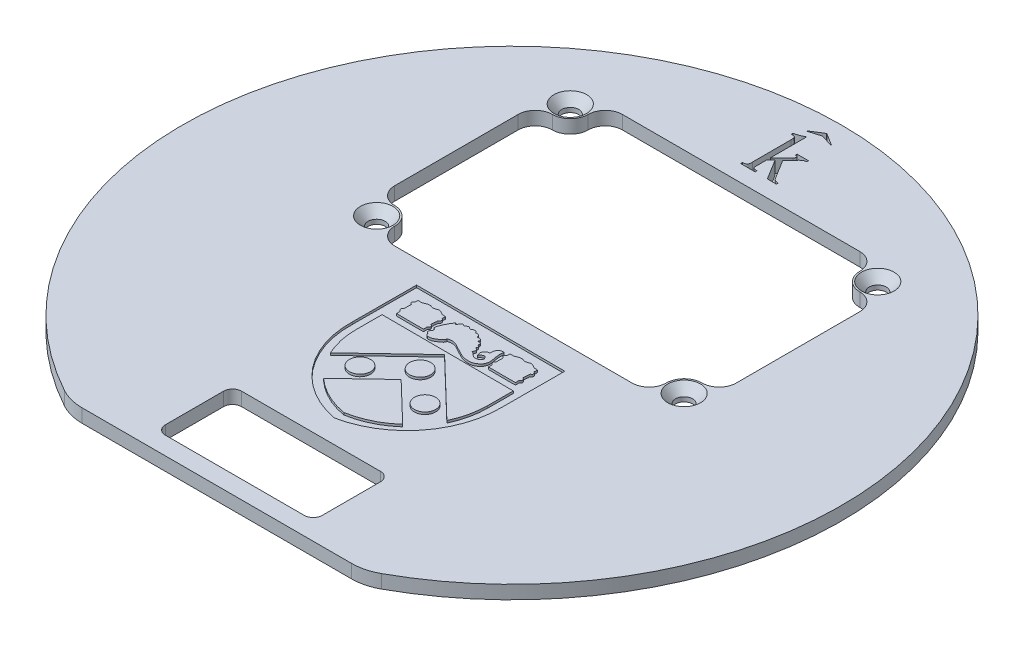
SolidWorks part; units mm, degrees
material "Acrylic (Medium-high impact)"
ref_plane "Front Plane" through (0, 0, 0) normal (0, 0, 1) x (1, 0, 0)
ref_plane "Top Plane" through (0, 0, 0) normal (0, 1, 0) x (1, 0, 0)
ref_plane "Right Plane" through (0, 0, 0) normal (1, 0, 0) x (0, 0, -1)
sketch "Sketch1" plane through (0, 0, 0) normal (0, 1, 0) x (1, 0, 0)
  line L0 (-30.03, -64.8129) -> (30.03, -64.8129) construction
  line L1 (0, -85) -> (0, 0) construction
  line L2 (0, -85) -> (32.4891, -64.8129) construction
  line L3 (-30.03, -65.8129) -> (30.03, -65.8129)
  arc A0 (34.8348, -63.5829) -> (-34.8348, -63.5829) centre (0, 0) ccw construction
  circle A1 centre (0, -85) radius 38.25 construction
  arc A2 (30.03, -64.8129) -> (34.8348, -63.5829) centre (30.03, -54.8129) ccw construction
  arc A3 (-30.03, -64.8129) -> (-34.8348, -63.5829) centre (-30.03, -54.8129) cw construction
  arc A4 (35.3153, -64.4599) -> (-35.3153, -64.4599) centre (0, 0) ccw
  arc A5 (-30.03, -65.8129) -> (-35.3153, -64.4599) centre (-30.03, -54.8129) cw
  arc A6 (30.03, -65.8129) -> (35.3153, -64.4599) centre (30.03, -54.8129) ccw
  dimension "D1" = 145
  dimension "D2" = 76.5
  dimension "D4" = 10
  dimension "D3" = 85
  dimension "D5" = 1
extrude "Boss-Extrude1" add sketch "Sketch1" along normal blind 3
sketch "Sketch2" plane through (0, 3, 0) normal (0, 1, 0) x (1, 0, 0)
  line L0 (-30.03, -65.8129) -> (30.03, -65.8129) construction
  line L1 (38.1, 0.3071) -> (-38.1, 0.3071) construction
  line L2 (38.1, 0.3071) -> (38.1, 51.1071) construction
  line L3 (38.1, 51.1071) -> (-38.1, 51.1071) construction
  line L4 (-38.1, 0.3071) -> (-38.1, 51.1071) construction
  line L5 (34.29, 4.1171) -> (-34.29, 4.1171) construction
  line L6 (-34.29, 4.1171) -> (-34.29, 47.2971) construction
  line L7 (34.29, 47.2971) -> (-34.29, 47.2971) construction
  line L8 (34.29, 4.1171) -> (34.29, 47.2971) construction
  line L9 (-38.1, 11.9271) -> (-38.1, 39.4871)
  line L10 (38.1, 11.9271) -> (38.1, 39.4871)
  line L11 (26.48, 51.1071) -> (-26.48, 51.1071)
  line L12 (-26.48, 0.3071) -> (26.48, 0.3071)
  line L14 (-15.5, -61.8129) -> (15.5, -61.8129)
  line L15 (-17.5, -59.8129) -> (-17.5, -46.8129)
  line L16 (-15.5, -44.8129) -> (15.5, -44.8129)
  line L17 (17.5, -59.8129) -> (17.5, -46.8129)
  circle A0 centre (34.29, 4.1171) radius 1.905
  circle A1 centre (-34.29, 4.1171) radius 1.905
  circle A2 centre (34.29, 47.2971) radius 1.905
  circle A3 centre (-34.29, 47.2971) radius 1.905
  arc A4 (30.29, 4.1171) -> (34.29, 8.1171) centre (34.29, 4.1171) cw
  arc A5 (34.29, 8.1171) -> (38.1, 11.9271) centre (34.29, 11.9271) ccw
  arc A6 (30.29, 4.1171) -> (26.48, 0.3071) centre (26.48, 4.1171) cw
  arc A7 (-38.1, 11.9271) -> (-34.29, 8.1171) centre (-34.29, 11.9271) ccw
  arc A8 (-34.29, 8.1171) -> (-30.29, 4.1171) centre (-34.29, 4.1171) cw
  arc A9 (-30.29, 4.1171) -> (-26.48, 0.3071) centre (-26.48, 4.1171) ccw
  arc A10 (-38.1, 39.4871) -> (-34.29, 43.2971) centre (-34.29, 39.4871) cw
  arc A11 (-34.29, 43.2971) -> (-30.29, 47.2971) centre (-34.29, 47.2971) ccw
  arc A12 (-30.29, 47.2971) -> (-26.48, 51.1071) centre (-26.48, 47.2971) cw
  arc A13 (38.1, 39.4871) -> (34.29, 43.2971) centre (34.29, 39.4871) ccw
  arc A14 (34.29, 43.2971) -> (30.29, 47.2971) centre (34.29, 47.2971) cw
  arc A15 (30.29, 47.2971) -> (26.48, 51.1071) centre (26.48, 47.2971) ccw
  arc A16 (15.5, -61.8129) -> (17.5, -59.8129) centre (15.5, -59.8129) ccw
  arc A17 (-15.5, -61.8129) -> (-17.5, -59.8129) centre (-15.5, -59.8129) cw
  arc A18 (-17.5, -46.8129) -> (-15.5, -44.8129) centre (-15.5, -46.8129) cw
  arc A19 (15.5, -44.8129) -> (17.5, -46.8129) centre (15.5, -46.8129) cw
  point P5 (0, 0.3071)
  point P8 (0, -65.8129)
  point P11 (0, 51.1071)
  point P46 (0, -61.8129)
  point P51 (17.5, -61.8129)
  point P56 (-17.5, -44.8129)
  point P59 (17.5, -44.8129)
  dimension "D5" = 3.81
  dimension "D6" = 4
  dimension "D10" = 2
  dimension "D1" = 66.12
  dimension "D2" = 76.2
  dimension "D3" = 50.8
  dimension "D7" = 17
  dimension "D8" = 35
  dimension "D9" = 4
  dimension "D4" = 3.81
extrude "Cut-Extrude1" cut sketch "Sketch2" against normal through all contours A2 | A1 | A0 | A14 A15 L11 A12 A11 A10 L9 A7 A8 A9 L12 A6 A4 A5 L10 A13 | L14 L17 L16 L15 | A3
sketch "Sketch3" plane through (0, 3, 0) normal (0, 1, 0) x (1, 0, 0)
  line L0 (0, 0.3071) -> (0, -4.8617) construction
  line L1 (-26.48, 0.3071) -> (26.48, 0.3071) construction
  line L2 (0, -39.644) -> (0, -44.8129) construction
  line L3 (-15.5, -44.8129) -> (15.5, -44.8129) construction
  line L4 (-31.076, 54.8036) -> (31.076, 54.8036) construction
  line L5 (26.48, 51.1071) -> (-26.48, 51.1071) construction
  line L6 (0, 54.8036) -> (0, 51.1071) construction
  line L7 (0, 51.1071) -> (0, 54.8036) construction
  line L8 (0, 54.8036) -> (0, 69.8036) construction
  line L9 (0, 69.8036) -> (0, 73.5) construction
  line L10 (-2.6931, 68.5353) -> (-0.0266, 70.2086)
  line L11 (0.0266, 70.2086) -> (2.6931, 68.5353)
  line L12 (2.6524, 68.445) -> (0, 69.2253)
  line L13 (0, 69.2253) -> (-2.6524, 68.445)
  line L14 (-3, 68.3428) -> (3, 68.3428) construction
  arc A0 (35.3153, -64.4599) -> (-35.3153, -64.4599) centre (0, 0) ccw construction
  arc A1 (-2.6931, 68.5353) -> (-2.6524, 68.445) centre (-2.6666, 68.493) ccw
  arc A2 (2.6931, 68.5353) -> (2.6524, 68.445) centre (2.6666, 68.493) cw
  arc A3 (-0.0266, 70.2086) -> (0.0266, 70.2086) centre (0, 70.1662) cw
  text T0 "k" font "Kozuka Mincho Pr6N R" height 12
  point P12 (0, 54.8036)
  point P13 (0, 51.1071)
  point P33 (0, 68.3428)
  point P51 (0, 70.2253)
  line B0 (0.08, -15.1067) -> (13.0745, -27.5884)
  line B1 (14.7618, -14.4609) -> (14.7432, -20.1499)
  line B2 (-14.5971, -14.3651) -> (14.7618, -14.4609)
  line B3 (-14.5971, -14.3651) -> (-14.6157, -20.0541)
  line B4 (-12.9956, -27.5034) -> (0.08, -15.1067)
  line B5 (-8.831, -33.1875) -> (0.0485, -24.7691)
  line B6 (0.0485, -24.7691) -> (8.873, -33.2453)
  line B7 (-16.471, -4.808) -> (10.8149, -4.897)
  line B8 (10.8149, -4.897) -> (16.6979, -4.9162)
  line B9 (16.6979, -4.9162) -> (16.6514, -19.1654)
  line B10 (-16.471, -4.808) -> (-16.4855, -9.2611)
  line B11 (-16.4855, -9.2611) -> (-16.5175, -19.0572)
  arc B12 (16.6514, -19.1654) -> (0, -39.644) centre (-4.072, -19.324) cw
  arc B13 (0, -39.644) -> (-16.5175, -19.0572) centre (3.8047, -19.6717) cw
  circle B14 centre (7.3201, -26.7085) radius 2.359
  circle B15 centre (-7.2355, -26.6611) radius 2.359
  circle B16 centre (0.0623, -20.5401) radius 2.359
  arc B17 (13.0745, -27.5884) -> (14.7432, -20.1499) centre (-2.9271, -20.0923) ccw
  arc B18 (-14.6157, -20.0541) -> (-12.9956, -27.5034) centre (3.0546, -20.1118) ccw
  arc B19 (-8.831, -33.1875) -> (0.0069, -37.5174) centre (3.0546, -20.1118) ccw
  arc B20 (0.0069, -37.5174) -> (8.873, -33.2453) centre (-2.9271, -20.0923) ccw
  spline B21 degree 3 poles (7.3575, -12.2799) (7.3558, -12.3337) (7.3522, -12.4081) (7.3498, -12.5007) (7.3552, -12.5482) (7.3512, -12.608) (7.429, -12.6029) (7.61, -12.598) (8.1433, -12.6141) (8.9182, -12.5935) (9.7622, -12.6227) (10.4121, -12.631) (10.8996, -12.6259) (11.3075, -12.6202) (11.6848, -12.6255) (12.0263, -12.6176) (12.3408, -12.6217) (12.6505, -12.6183) (12.9399, -12.6033) (13.1638, -12.6141) (13.3495, -12.5982) (13.3983, -12.4289) (13.3774, -12.2509) (13.3888, -12.0533) (13.377, -11.8824) (13.4083, -11.7477) (13.5237, -11.6535) (13.6281, -11.5222) (13.725, -11.3413) (13.6651, -11.1595) (13.5859, -11.0135) (13.4396, -10.9573) (13.2676, -10.915) (13.3218, -10.6737) (13.3251, -10.4115) (13.334, -10.0593) (13.406, -9.7503) (13.3793, -9.5061) (13.432, -9.289) (13.6077, -9.2353) (13.7581, -9.0855) (13.6985, -8.8874) (13.7353, -8.6994) (13.6358, -8.6057) (13.5345, -8.5375) (13.3516, -8.5012) (13.4504, -8.281) (13.4161, -8.0576) (13.4296, -7.918) (13.4248, -7.8079) knots 0.498851 0.498851 0.498851 0.498851 0.505805 0.508518 0.510587 0.512309 0.514944 0.518128 0.537691 0.580942 0.619698 0.645982 0.664757 0.682489 0.69855 0.713362 0.726504 0.739021 0.753421 0.763225 0.769274 0.77445 0.783248 0.792986 0.799593 0.805527 0.809722 0.81828 0.827589 0.833982 0.842185 0.847586 0.854463 0.860726 0.874345 0.89073 0.905222 0.914604 0.922885 0.930829 0.936714 0.948198 0.954622 0.959784 0.964103 0.971407 0.977534 0.989081 1 1 1 1
  spline B22 degree 3 poles (13.4248, -7.8079) (13.4246, -7.8037) (13.4226, -7.7612) (13.4211, -7.7053) (13.3521, -7.7177) (13.2772, -7.7184) (13.132, -7.7123) (12.9243, -7.7211) (12.7008, -7.6925) (12.5016, -7.6074) (12.3232, -7.5297) (12.1565, -7.4305) (12.009, -7.3408) (11.849, -7.2749) (11.7105, -7.1764) (11.5489, -7.199) (11.3974, -7.1797) (11.2255, -7.2499) (11.0114, -7.3207) (10.7466, -7.4065) (10.483, -7.4835) (10.2302, -7.4862) (10.0228, -7.4247) (9.8352, -7.3424) (9.6113, -7.2305) (9.3487, -7.3048) (9.0742, -7.2835) (8.8328, -7.4026) (8.5613, -7.4866) (8.293, -7.6246) (8.0051, -7.7084) (7.7466, -7.6769) (7.5377, -7.6921) (7.3886, -7.6832) (7.2392, -7.7058) (7.2317, -7.8747) (7.2248, -8.0258) (7.2323, -8.1804) (7.2125, -8.3811) (6.9768, -8.4627) (6.8226, -8.7059) (6.907, -8.9546) (7.0619, -9.0776) (7.2108, -9.1313) (7.2933, -9.3283) (7.2221, -9.7522) (7.2461, -10.2027) (7.2426, -10.5859) (7.2553, -10.7045) (7.2479, -10.7998) (7.1289, -10.8876) (6.9994, -11.0226) (6.9247, -11.2248) (6.9853, -11.3683) (7.0387, -11.4642) (7.0811, -11.5686) (7.2149, -11.586) (7.246, -11.709) (7.3447, -11.7367) (7.3684, -11.8417) (7.3611, -12.0141) (7.3609, -12.174) (7.3575, -12.2799) knots 0 0 0 0 0.000416 0.004158 0.00592 0.008172 0.014222 0.02432 0.03513 0.042797 0.052138 0.060174 0.067794 0.074267 0.082645 0.088397 0.094591 0.102071 0.111697 0.123859 0.137901 0.146871 0.156007 0.165456 0.173526 0.187207 0.19868 0.208401 0.22111 0.23537 0.247248 0.258945 0.268632 0.27384 0.278899 0.285383 0.291981 0.29935 0.305497 0.315905 0.327706 0.339032 0.345871 0.353016 0.358205 0.371688 0.407261 0.416587 0.420857 0.42273 0.428556 0.438117 0.447643 0.453771 0.457355 0.4621 0.467135 0.472154 0.476238 0.478457 0.485178 0.498851 0.498851 0.498851 0.498851
  spline B23 degree 3 poles (-13.2164, -12.2127) (-13.2181, -12.2666) (-13.2217, -12.3409) (-13.2241, -12.4336) (-13.2187, -12.481) (-13.2227, -12.5409) (-13.1449, -12.5358) (-12.9639, -12.5308) (-12.4306, -12.547) (-11.6557, -12.5264) (-10.8117, -12.5556) (-10.1618, -12.5639) (-9.6743, -12.5588) (-9.2664, -12.553) (-8.8891, -12.5584) (-8.5476, -12.5505) (-8.2331, -12.5546) (-7.9234, -12.5512) (-7.634, -12.5362) (-7.4101, -12.547) (-7.2243, -12.5311) (-7.1756, -12.3618) (-7.1965, -12.1838) (-7.1851, -11.9861) (-7.1969, -11.8153) (-7.1656, -11.6805) (-7.0502, -11.5864) (-6.9458, -11.4551) (-6.8489, -11.2742) (-6.9087, -11.0924) (-6.988, -10.9463) (-7.1343, -10.8902) (-7.3063, -10.8479) (-7.2521, -10.6065) (-7.2488, -10.3444) (-7.2399, -9.9921) (-7.1679, -9.6832) (-7.1946, -9.439) (-7.1419, -9.2219) (-6.9662, -9.1682) (-6.8158, -9.0184) (-6.8754, -8.8203) (-6.8386, -8.6322) (-6.9381, -8.5385) (-7.0394, -8.4704) (-7.2223, -8.4341) (-7.1235, -8.2139) (-7.1578, -7.9904) (-7.1443, -7.8509) (-7.1491, -7.7408) knots 0.498851 0.498851 0.498851 0.498851 0.505805 0.508518 0.510587 0.512309 0.514944 0.518128 0.537691 0.580942 0.619698 0.645982 0.664757 0.682489 0.69855 0.713362 0.726504 0.739021 0.753421 0.763225 0.769274 0.77445 0.783248 0.792986 0.799593 0.805527 0.809722 0.81828 0.827589 0.833982 0.842185 0.847586 0.854463 0.860726 0.874345 0.89073 0.905222 0.914604 0.922885 0.930829 0.936714 0.948198 0.954622 0.959784 0.964103 0.971407 0.977534 0.989081 1 1 1 1
  spline B24 degree 3 poles (-7.1491, -7.7408) (-7.1493, -7.7366) (-7.1513, -7.6941) (-7.1528, -7.6382) (-7.2218, -7.6506) (-7.2967, -7.6513) (-7.4419, -7.6452) (-7.6496, -7.6539) (-7.8731, -7.6253) (-8.0723, -7.5403) (-8.2507, -7.4626) (-8.4174, -7.3633) (-8.5649, -7.2737) (-8.7249, -7.2078) (-8.8634, -7.1093) (-9.025, -7.1319) (-9.1765, -7.1126) (-9.3484, -7.1828) (-9.5625, -7.2536) (-9.8273, -7.3394) (-10.0908, -7.4164) (-10.3437, -7.4191) (-10.5511, -7.3576) (-10.7387, -7.2753) (-10.9625, -7.1634) (-11.2252, -7.2377) (-11.4997, -7.2164) (-11.7411, -7.3355) (-12.0126, -7.4195) (-12.2809, -7.5575) (-12.5687, -7.6413) (-12.8273, -7.6098) (-13.0362, -7.625) (-13.1853, -7.6161) (-13.3347, -7.6387) (-13.3422, -7.8076) (-13.3491, -7.9587) (-13.3416, -8.1133) (-13.3614, -8.314) (-13.5971, -8.3956) (-13.7513, -8.6388) (-13.6669, -8.8875) (-13.512, -9.0105) (-13.3631, -9.0642) (-13.2806, -9.2611) (-13.3518, -9.6851) (-13.3278, -10.1356) (-13.3313, -10.5188) (-13.3186, -10.6374) (-13.326, -10.7327) (-13.445, -10.8205) (-13.5745, -10.9555) (-13.6492, -11.1577) (-13.5885, -11.3012) (-13.5352, -11.3971) (-13.4928, -11.5015) (-13.359, -11.5189) (-13.3279, -11.6419) (-13.2292, -11.6696) (-13.2055, -11.7745) (-13.2128, -11.947) (-13.213, -12.1069) (-13.2164, -12.2127) knots 0 0 0 0 0.000416 0.004158 0.00592 0.008172 0.014222 0.02432 0.03513 0.042797 0.052138 0.060174 0.067794 0.074267 0.082645 0.088397 0.094591 0.102071 0.111697 0.123859 0.137901 0.146871 0.156007 0.165456 0.173526 0.187207 0.19868 0.208401 0.22111 0.23537 0.247248 0.258945 0.268632 0.27384 0.278899 0.285383 0.291981 0.29935 0.305497 0.315905 0.327706 0.339032 0.345871 0.353016 0.358205 0.371688 0.407261 0.416587 0.420857 0.42273 0.428556 0.438117 0.447643 0.453771 0.457355 0.4621 0.467135 0.472154 0.476238 0.478457 0.485178 0.498851 0.498851 0.498851 0.498851
  spline B25 degree 3 poles (3.5292, -12.1354) (3.4202, -12.0628) (3.1621, -11.9083) (2.9854, -11.6007) (2.5279, -11.4795) (2.6583, -11.298) (2.7103, -11.1417) (2.836, -10.9075) (2.7214, -10.5934) (2.5475, -10.3986) (2.1701, -10.3072) (2.3142, -10.1862) (2.4097, -10.0758) (2.3906, -9.8607) (2.2747, -9.6136) (1.9275, -9.6432) (1.9801, -9.44) (1.9652, -9.3071) (1.9883, -9.1302) (1.9025, -8.9216) (1.6618, -8.7985) (1.4837, -8.812) (1.1564, -8.8558) (1.2544, -8.7557) (1.2958, -8.6649) (1.3019, -8.4908) (1.2229, -8.2808) (1.078, -8.0472) (0.8382, -8.097) (0.6479, -8.0435) (0.4667, -8.0921) (0.2619, -8.0619) (0.266, -7.8376) (0.1957, -7.6302) (-0.0158, -7.4249) (-0.3009, -7.408) (-0.5048, -7.4159) (-0.6552, -7.5771) (-0.6484, -7.3655) (-0.7476, -7.2825) (-0.8267, -7.1252) (-1.0712, -7.0383) (-1.365, -7.0586) (-1.7217, -7.0774) (-1.8194, -7.3397) (-2.0531, -7.3669) (-2.2284, -7.1648) (-2.5254, -6.972) (-2.895, -7.113) (-3.089, -7.2848) (-3.2535, -7.4732) (-3.4201, -7.3427) (-3.5817, -7.1671) (-3.9085, -7.1778) (-4.0315, -7.387) (-4.1787, -7.5164) (-4.2629, -7.7592) (-4.4071, -7.9006) (-4.5282, -8.0641) (-4.6616, -7.9744) (-4.606, -7.8421) (-4.7416, -7.756) (-4.8511, -7.8757) (-4.9985, -7.9748) (-5.0682, -8.2218) (-5.2529, -8.3934) (-5.344, -8.6533) (-5.5344, -8.8662) (-5.5921, -9.1177) (-5.7331, -9.3191) (-5.8188, -9.5548) (-5.9698, -9.89) (-6.0699, -10.2349) (-6.2447, -10.5525) (-6.2485, -10.8406) (-6.2932, -11.2014) (-6.0422, -11.2473) (-5.9366, -11.3621) (-5.8764, -11.519) (-5.8982, -11.6876) (-5.9157, -11.8872) (-6.0858, -12.0166) (-6.1935, -12.1707) (-6.2513, -12.3415) (-6.3019, -12.4899) (-6.2636, -12.6505) (-6.1291, -12.7272) (-6.022, -12.8315) (-5.843, -12.8366) (-5.8439, -12.9674) (-5.837, -13.0708) (-5.7456, -13.1798) (-5.6572, -13.3066) (-5.5041, -13.4082) (-5.3407, -13.4923) (-5.1498, -13.4687) (-4.9693, -13.4694) (-4.7861, -13.4377) (-4.6072, -13.4136) (-4.4313, -13.3455) (-4.262, -13.2649) (-4.1018, -13.1705) (-3.9483, -13.0915) (-3.7983, -12.9908) (-3.6285, -12.8897) (-3.4606, -12.78) (-3.3066, -12.6198) (-3.0936, -12.5076) (-2.8908, -12.3425) (-2.7755, -12.1627) (-2.7113, -12.0077) (-2.7044, -11.8842) (-2.6458, -11.837) (-2.6275, -11.8237) knots 0.50354 0.50354 0.50354 0.50354 0.51161 0.522207 0.528988 0.530284 0.535245 0.540022 0.546492 0.554232 0.559496 0.561431 0.564066 0.569048 0.573906 0.580531 0.582626 0.585519 0.589375 0.593764 0.599166 0.604469 0.60898 0.610227 0.611694 0.61564 0.620621 0.62666 0.630204 0.635076 0.638903 0.642599 0.645688 0.651375 0.656858 0.663245 0.66869 0.670475 0.673631 0.67647 0.679384 0.684316 0.691668 0.699024 0.704595 0.706452 0.713005 0.720109 0.727879 0.735425 0.738141 0.741637 0.746253 0.754491 0.756829 0.761481 0.766876 0.772388 0.77547 0.777349 0.78036 0.782863 0.784516 0.78978 0.794242 0.800093 0.805463 0.811531 0.817965 0.821499 0.827139 0.833929 0.844988 0.850269 0.856356 0.864597 0.867348 0.871178 0.874119 0.877799 0.881988 0.886256 0.890734 0.893904 0.897771 0.900648 0.903553 0.907181 0.910482 0.912347 0.914501 0.917163 0.921063 0.924402 0.928832 0.932379 0.936418 0.940421 0.94424 0.947936 0.952415 0.956245 0.959825 0.963452 0.967794 0.972484 0.976226 0.981897 0.987766 0.992766 0.995332 0.998583 1 1 1 1
  spline B26 degree 3 poles (-2.6275, -11.8237) (-2.5152, -11.7418) (-2.2682, -11.6574) (-1.8799, -11.6189) (-1.4933, -11.6057) (-1.1034, -11.6799) (-0.7339, -11.7891) (-0.4009, -12.0029) (-0.0118, -12.1807) (0.431, -12.4511) (0.9539, -12.6921) (1.4786, -13.0041) (2.0164, -13.2667) (2.575, -13.5042) (3.2151, -13.6462) (3.8751, -13.6956) (4.5458, -13.6757) (5.1198, -13.4476) (5.6028, -13.1621) (6.0127, -12.8257) (6.3015, -12.3803) (6.4467, -11.9577) (6.5556, -11.4034) (6.4745, -10.8244) (6.3269, -10.1768) (6.2516, -9.625) (6.2029, -9.1621) (6.1775, -8.7227) (6.2357, -8.4139) (6.2872, -8.1993) (6.2925, -8.043) (6.1112, -8.0605) (5.9414, -8.0329) (5.7417, -8.077) (5.4774, -8.1371) (5.1669, -8.3575) (4.9184, -8.8285) (4.8359, -9.3183) (4.839, -9.6186) (4.8242, -9.7941) (4.6886, -9.7624) (4.5717, -9.798) (4.4032, -9.8447) (4.2089, -9.9476) (3.9863, -10.1002) (3.8477, -10.3184) (3.7397, -10.5178) (3.6792, -10.7378) (3.7282, -10.9604) (3.7575, -11.1825) (3.7887, -11.3689) (3.8552, -11.465) (3.8803, -11.6049) (3.932, -11.4857) (3.986, -11.416) (4.0711, -11.3034) (4.2108, -11.1779) (4.3921, -11.0505) (4.6143, -10.9402) (4.9115, -10.899) (5.108, -11.1231) (5.3198, -11.3633) (5.3679, -11.7348) (5.1613, -12.0503) (4.8521, -12.289) (4.4237, -12.3354) (3.9333, -12.4285) (3.667, -12.2272) (3.5292, -12.1354) knots 0 0 0 0 0.008696 0.016351 0.024972 0.033314 0.041663 0.049422 0.058482 0.069011 0.08257 0.095276 0.108036 0.120861 0.134014 0.149754 0.163233 0.176471 0.188702 0.199144 0.21007 0.222174 0.227546 0.246109 0.258739 0.270213 0.281693 0.288503 0.298433 0.301049 0.303481 0.306413 0.310113 0.315317 0.318982 0.327539 0.338482 0.352538 0.357683 0.359515 0.36177 0.364544 0.367746 0.372777 0.378626 0.384734 0.389046 0.393177 0.398998 0.403225 0.407863 0.410164 0.411894 0.413633 0.415371 0.418457 0.422209 0.427514 0.432475 0.438269 0.444894 0.44994 0.459009 0.466064 0.473296 0.483196 0.493331 0.50354 0.50354 0.50354 0.50354
  dimension "D4" = 0.05
  dimension "D1" = 15
  dimension "D2" = 6
  dimension "D3" = 1
sketch_block_instance "Block2-1"
sketch_block "Block2"
extrude "Cut-Extrude2" cut sketch "Sketch3" against normal blind 0.5
sketch "Sketch4" plane through (0, 2.5, 0) normal (0, 1, 0) x (1, 0, 0)
  line L4 (-2.6524, 68.445) -> (0, 69.2253)
  line L5 (0, 69.2253) -> (2.6524, 68.445)
  line L6 (2.6931, 68.5353) -> (0.0266, 70.2086)
  line L7 (-0.0266, 70.2086) -> (-2.6931, 68.5353)
  line L8 (-2.6524, 68.445) -> (0, 69.2253)
  line L9 (0, 69.2253) -> (2.6524, 68.445)
  line L10 (2.6931, 68.5353) -> (0.0266, 70.2086)
  line L11 (-0.0266, 70.2086) -> (-2.6931, 68.5353)
  line L19 (-1.5887, 59.2473) -> (-1.5887, 67.1644)
  line L20 (-1.5887, 67.1644) -> (-1.7557, 67.2785)
  line L21 (-3.8308, 66.51) -> (-3.8292, 66.1081)
  line L22 (-2.7756, 64.9588) -> (-2.7733, 56.4492)
  line L23 (-3.8308, 55.2454) -> (-3.8292, 54.813)
  line L24 (-3.8292, 54.813) -> (-0.5813, 54.813)
  line L25 (-0.5813, 54.813) -> (-0.5813, 55.2454)
  line L26 (-1.5887, 56.4323) -> (-1.5887, 58.3363)
  line L27 (-1.5887, 58.3363) -> (-0.63, 59.3286)
  line L28 (-0.63, 59.3286) -> (2.1435, 54.813)
  line L29 (2.1435, 54.813) -> (4.1667, 54.813)
  line L30 (4.1667, 54.813) -> (4.1667, 55.23)
  line L31 (2.8626, 55.9434) -> (0.28, 60.1258)
  line L32 (0.28, 60.1258) -> (2.0651, 61.9478)
  line L33 (3.2221, 62.4817) -> (3.2245, 62.9165)
  line L34 (3.2245, 62.9165) -> (0.6863, 62.9165)
  line L35 (0.6863, 62.9165) -> (0.6863, 62.4841)
  line L36 (0.9354, 61.7672) -> (-1.5562, 59.2473)
  line L37 (-1.5562, 59.2473) -> (-1.5887, 59.2473)
  line L38 (-1.5887, 59.2473) -> (-1.5887, 67.1644)
  line L39 (-1.5887, 67.1644) -> (-1.7557, 67.2785)
  line L40 (-3.8308, 66.51) -> (-3.8292, 66.1081)
  line L41 (-2.7756, 64.9588) -> (-2.7733, 56.4492)
  line L42 (-3.8308, 55.2454) -> (-3.8292, 54.813)
  line L43 (-3.8292, 54.813) -> (-0.5813, 54.813)
  line L44 (-0.5813, 54.813) -> (-0.5813, 55.2454)
  line L45 (-1.5887, 56.4323) -> (-1.5887, 58.3363)
  line L46 (-1.5887, 58.3363) -> (-0.63, 59.3286)
  line L47 (-0.63, 59.3286) -> (2.1435, 54.813)
  line L48 (2.1435, 54.813) -> (4.1667, 54.813)
  line L49 (4.1667, 54.813) -> (4.1667, 55.23)
  line L50 (2.8626, 55.9434) -> (0.28, 60.1258)
  line L51 (0.28, 60.1258) -> (2.0651, 61.9478)
  line L52 (3.2221, 62.4817) -> (3.2245, 62.9165)
  line L53 (3.2245, 62.9165) -> (0.6863, 62.9165)
  line L54 (0.6863, 62.9165) -> (0.6863, 62.4841)
  line L55 (0.9354, 61.7672) -> (-1.5562, 59.2473)
  line L56 (-1.5562, 59.2473) -> (-1.5887, 59.2473)
  arc A3 (2.6524, 68.445) -> (2.6931, 68.5353) centre (2.6666, 68.493) ccw
  arc A4 (0.0266, 70.2086) -> (-0.0266, 70.2086) centre (0, 70.1662) ccw
  arc A5 (-2.6931, 68.5353) -> (-2.6524, 68.445) centre (-2.6666, 68.493) ccw
  arc A6 (2.6524, 68.445) -> (2.6931, 68.5353) centre (2.6666, 68.493) ccw
  arc A7 (0.0266, 70.2086) -> (-0.0266, 70.2086) centre (0, 70.1662) ccw
  arc A8 (-2.6931, 68.5353) -> (-2.6524, 68.445) centre (-2.6666, 68.493) ccw
  spline S8 degree 3 poles (1604.661, -2466.1973) (-5.2342, 104.5272) (5.3927, 71.1887) (-2.2224, 66.9948) (-2.4641, 66.8819) (-2.7106, 66.7811) (-2.9696, 66.6972) (-3.2415, 66.6219) (-13.2985, 64.3805) (-29.0359, 93.8845) (503.62, -2889.9927) knots -11.300559 -11.300559 -11.300559 -11.300559 0.124024 0.24557 0.364216 0.482262 0.603077 0.729724 0.861233 14.436154 14.436154 14.436154 14.436154 only from (-1.7557, 67.2785) to (-3.8308, 66.51)
  spline S9 degree 3 poles (1.5359, 3065.8999) (-19.9864, 45.3767) (-11.6713, 66.3328) (-3.5189, 66.1048) (-3.3835, 66.0944) (-3.2652, 66.0728) (-3.1609, 66.0473) (-3.0716, 66.0143) (-3.0003, 65.9677) (-2.9399, 65.9175) (-2.8933, 65.8519) (-2.8572, 65.7717) (-2.8269, 65.6753) (-2.8007, 65.5639) (-2.7864, 65.4354) (-2.773, 65.2913) (-2.7623, 54.6654) (-19.9207, 45.3396) (2986.6257, -184.4592) knots -12.510714 -12.510714 -12.510714 -12.510714 0.086062 0.164462 0.234522 0.297932 0.352277 0.402298 0.445778 0.484825 0.524254 0.570263 0.621761 0.682057 0.748728 0.823668 0.908161 17.3405 17.3405 17.3405 17.3405 only from (-3.8292, 66.1081) to (-2.7756, 64.9588)
  spline S10 degree 3 poles (2994.8986, 171.1123) (-22.1045, 75.177) (-2.7027, 65.9429) (-2.7714, 56.1023) (-2.7816, 55.9518) (-2.7938, 55.818) (-2.8176, 55.7018) (-2.8458, 55.6021) (-2.8771, 55.5175) (-2.9211, 55.4486) (-2.9775, 55.3918) (-3.0507, 55.3475) (-3.1386, 55.3103) (-3.2433, 55.2793) (-3.3665, 55.2599) (-3.5062, 55.2455) (-11.1767, 55.0645) (-18.3439, 78.7237) (-83.7343, -2943.4897) knots -14.627727 -14.627727 -14.627727 -14.627727 0.092721 0.178071 0.254078 0.320834 0.381273 0.433047 0.477729 0.517183 0.555737 0.597828 0.645608 0.69999 0.762542 0.834015 0.91228 12.361008 12.361008 12.361008 12.361008 only from (-2.7733, 56.4492) to (-3.8308, 55.2454)
  spline S11 degree 3 poles (120.67, -2942.1526) (13.391, 78.0344) (6.6544, 55.0841) (-0.8904, 55.2451) (-1.0227, 55.2609) (-1.1397, 55.277) (-1.2409, 55.3056) (-1.3245, 55.3425) (-1.3941, 55.3854) (-1.4481, 55.4392) (-1.4898, 55.5069) (-1.5209, 55.5903) (-1.5494, 55.6891) (-1.5699, 55.8049) (-1.583, 55.9377) (-1.5927, 56.0874) (-1.689, 64.0206) (22.5496, 71.404) (-3000.2372, 141.2771) knots -11.490265 -11.490265 -11.490265 -11.490265 0.086118 0.162918 0.231541 0.293238 0.34646 0.394461 0.435019 0.472927 0.511803 0.557734 0.610956 0.671658 0.740281 0.818413 0.904931 13.073342 13.073342 13.073342 13.073342 only from (-0.5813, 55.2454) to (-1.5887, 56.4323)
  spline S12 degree 3 poles (-109.6219, -2942.44) (16.301, 92.3342) (9.2418, 54.5237) (3.7913, 55.248) (3.6171, 55.2811) (3.451, 55.3379) (3.2902, 55.4263) (3.1417, 55.5625) (-1.171, 60.5019) (29.0721, 90.5284) (-2433.1006, -1694.8417) knots -10.038545 -10.038545 -10.038545 -10.038545 0.123052 0.239595 0.350212 0.458647 0.570955 0.695087 0.838212 12.95981 12.95981 12.95981 12.95981 only from (4.1667, 55.23) to (2.8626, 55.9434)
  spline S13 degree 3 poles (-2073.3776, 2227.9657) (13.4065, 31.0032) (-2.7981, 57.8444) (2.3369, 62.2002) (2.4713, 62.2963) (2.6063, 62.3692) (2.7465, 62.4215) (2.8945, 62.4591) (8.2769, 63.1904) (15.4183, 29.9074) (-140.4478, 3058.9414) knots -14.885163 -14.885163 -14.885163 -14.885163 0.148034 0.285829 0.4099 0.523094 0.63362 0.749434 0.869883 12.950324 12.950324 12.950324 12.950324 only from (2.0651, 61.9478) to (3.2221, 62.4817)
  spline S14 degree 3 poles (-27.4424, 3062.239) (-13.1417, 42.606) (-6.1407, 62.9244) (0.9462, 62.4725) (1.0511, 62.4555) (1.138, 62.4373) (1.2027, 62.4057) (1.2515, 62.3706) (2.075, 61.0373) (-32.2876, 51.8173) (2928.94, 715.6883) knots -30.341649 -30.341649 -30.341649 -30.341649 0.204855 0.386221 0.541621 0.668244 0.770499 0.853102 0.928018 7.27483 7.27483 7.27483 7.27483 only from (0.6863, 62.4841) to (1.2809, 62.2725)
  spline S15 degree 3 poles (2829.9235, -936.7362) (-32.6389, 80.1041) (2.7542, 64.5207) (1.1865, 62.0438) (-3.2237, 56.6964) (-32.974, 72.301) (2302.5681, -1862.2927) knots -13.20099 -13.20099 -13.20099 -13.20099 0.162941 0.379217 0.655651 33.643 33.643 33.643 33.643 only from (1.2809, 62.2725) to (0.9354, 61.7672)
  spline S16 degree 3 poles (-1.7557, 67.2785) (-1.8325, 67.2272) (-1.9846, 67.1257) (-2.2224, 66.9948) (-2.4641, 66.8819) (-2.7106, 66.7811) (-2.9696, 66.6972) (-3.2415, 66.6219) (-3.5301, 66.5576) (-3.7288, 66.5261) (-3.8308, 66.51) knots 0 0 0 0 0.124024 0.24557 0.364216 0.482262 0.603077 0.729724 0.861233 1 1 1 1
  spline S17 degree 3 poles (-3.8292, 66.1081) (-3.7741, 66.1084) (-3.6689, 66.109) (-3.5189, 66.1048) (-3.3835, 66.0944) (-3.2652, 66.0728) (-3.1609, 66.0473) (-3.0716, 66.0143) (-3.0003, 65.9677) (-2.9399, 65.9175) (-2.8933, 65.8519) (-2.8572, 65.7717) (-2.8269, 65.6753) (-2.8007, 65.5639) (-2.7864, 65.4354) (-2.773, 65.2913) (-2.7728, 65.1304) (-2.7746, 65.0176) (-2.7756, 64.9588) knots 0 0 0 0 0.086062 0.164462 0.234522 0.297932 0.352277 0.402298 0.445778 0.484825 0.524254 0.570263 0.621761 0.682057 0.748728 0.823668 0.908161 1 1 1 1
  spline S18 degree 3 poles (-2.7733, 56.4492) (-2.7722, 56.388) (-2.7702, 56.2703) (-2.7714, 56.1023) (-2.7816, 55.9518) (-2.7938, 55.818) (-2.8176, 55.7018) (-2.8458, 55.6021) (-2.8771, 55.5175) (-2.9211, 55.4486) (-2.9775, 55.3918) (-3.0507, 55.3475) (-3.1386, 55.3103) (-3.2433, 55.2793) (-3.3665, 55.2599) (-3.5062, 55.2455) (-3.6632, 55.2418) (-3.7729, 55.2442) (-3.8308, 55.2454) knots 0 0 0 0 0.092721 0.178071 0.254078 0.320834 0.381273 0.433047 0.477729 0.517183 0.555737 0.597828 0.645608 0.69999 0.762542 0.834015 0.91228 1 1 1 1
  spline S19 degree 3 poles (-0.5813, 55.2454) (-0.6366, 55.2442) (-0.7413, 55.2419) (-0.8904, 55.2451) (-1.0227, 55.2609) (-1.1397, 55.277) (-1.2409, 55.3056) (-1.3245, 55.3425) (-1.3941, 55.3854) (-1.4481, 55.4392) (-1.4898, 55.5069) (-1.5209, 55.5903) (-1.5494, 55.6891) (-1.5699, 55.8049) (-1.583, 55.9377) (-1.5927, 56.0874) (-1.5947, 56.2545) (-1.5908, 56.3712) (-1.5887, 56.4323) knots 0 0 0 0 0.086118 0.162918 0.231541 0.293238 0.34646 0.394461 0.435019 0.472927 0.511803 0.557734 0.610956 0.671658 0.740281 0.818413 0.904931 1 1 1 1
  spline S20 degree 3 poles (4.1667, 55.23) (4.1017, 55.2278) (3.9751, 55.2235) (3.7913, 55.248) (3.6171, 55.2811) (3.451, 55.3379) (3.2902, 55.4263) (3.1417, 55.5625) (2.9924, 55.7336) (2.9076, 55.8707) (2.8626, 55.9434) knots 0 0 0 0 0.123052 0.239595 0.350212 0.458647 0.570955 0.695087 0.838212 1 1 1 1
  spline S21 degree 3 poles (2.0651, 61.9478) (2.1109, 61.9941) (2.1993, 62.0835) (2.3369, 62.2002) (2.4713, 62.2963) (2.6063, 62.3692) (2.7465, 62.4215) (2.8945, 62.4591) (3.0546, 62.4809) (3.1649, 62.4814) (3.2221, 62.4817) knots 0 0 0 0 0.148034 0.285829 0.4099 0.523094 0.63362 0.749434 0.869883 1 1 1 1
  spline S22 degree 3 poles (0.6863, 62.4841) (0.7333, 62.4828) (0.8219, 62.4804) (0.9462, 62.4725) (1.0511, 62.4555) (1.138, 62.4373) (1.2027, 62.4057) (1.2515, 62.3706) (1.2806, 62.3236) (1.2808, 62.2893) (1.2809, 62.2725) knots 0 0 0 0 0.204855 0.386221 0.541621 0.668244 0.770499 0.853102 0.928018 1 1 1 1
  spline S23 degree 3 poles (1.2809, 62.2725) (1.2748, 62.239) (1.2607, 62.161) (1.1865, 62.0438) (1.0763, 61.9101) (0.9856, 61.8182) (0.9354, 61.7672) knots 0 0 0 0 0.162941 0.379217 0.655651 1 1 1 1
  dimension "D1" = 0
  dimension "D2" = 0
extrude "Cut-Extrude3" cut sketch "Sketch4" against normal through all
chamfer "Chamfer1" distance 2 angle 41 4 edges at (-34.29, 3, -2.2121) (34.29, 3, -2.2121) (34.29, 3, -45.3921) (-34.29, 3, -45.3921)
equation "\"smallPulleyTeeth\"= 30"
equation "\"largePulleyTeeth\"= 30"
equation "\"eighthThick\"= 3.0mm"
equation "\"sixteenthThick\"= 1.7mm"
equation "\"quarterThick\"=6.0mm"
equation "\"OD\"= 145mm"
equation "\"puckAngle\"= 60.5deg"
equation "\"puckDiam\"= 76.5mm"
equation "\"axlePress\"= 5.9mm"
equation "\"press\"= 0.2mm"
equation "\"wheelClear\"= 0.3mm"
equation "\"10-32clear\"= 4.8mm"
equation "\"6-32clear\"= 3.3mm"
equation "\"8-32clear\"= 4.0mm"
equation "\"4-40clear\"= 3.0mm"
equation "\"wheelHeight\"= 22mm"
equation "\"wheelWell\"= 65mm"
equation "\"D1@Sketch1\"=\"OD\""
equation "\"D1@Boss-Extrude1\"=\"eighthThick\""
equation "\"D2@Sketch1\"=\"puckDiam\""
equation "\"puckDist\"= 85mm"
equation "\"scoopFillet\"= 5mm"
equation "\"10-32tap\"= 4.45mm"
equation "\"ledSmall\"= 3.1mm"
equation "\"ledLarge\"= 4.2mm"
equation "\"ledLength\"= 4.2mm"
equation "\"D3@Sketch1\"=\"puckDist\""
